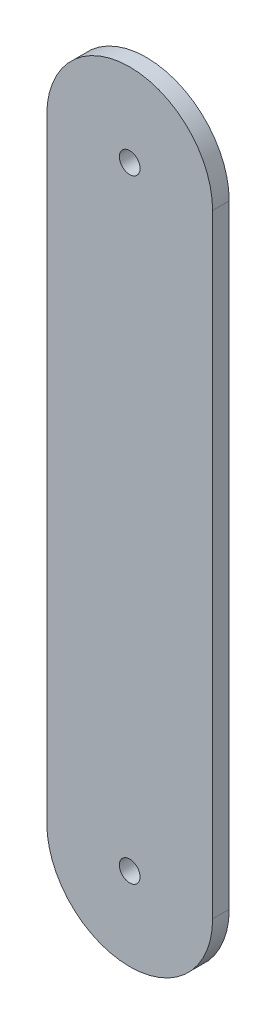
SolidWorks part; units mm, degrees
material "自訂玻璃纖維"
ref_plane "前基準面" through (0, 0, 0) normal (0, 0, 1) x (1, 0, 0)
ref_plane "上基準面" through (0, 0, 0) normal (0, 1, 0) x (1, 0, 0)
ref_plane "右基準面" through (0, 0, 0) normal (1, 0, 0) x (0, 0, -1)
sketch "草圖1" plane through (0, 0, 0) normal (0, 0, 1) x (1, 0, 0)
  line L2 (-28.6834, 37.2568) -> (-28.6834, -36.7432)
  line L4 (-8.6834, 37.2568) -> (-8.6834, -36.7432)
  arc A0 (-8.6834, 37.2568) -> (-28.6834, 37.2568) centre (-18.6834, 37.2568) ccw
  arc A1 (-8.6834, -36.7432) -> (-28.6834, -36.7432) centre (-18.6834, -36.7432) cw
  circle A2 centre (-18.6834, 37.2568) radius 1.25
  circle A3 centre (-18.6834, -36.7432) radius 1.25
  point P4 (-18.6834, 37.2568)
  point P5 (-18.6834, -36.7432)
  dimension "D1" = 2.5
  dimension "D2" = 2.5
  dimension "D3" = 10
  dimension "D6" = 0
  dimension "D4" = 74
  dimension "D5" = 74
extrude "填料-伸長1" add sketch "草圖1" along normal blind 2
